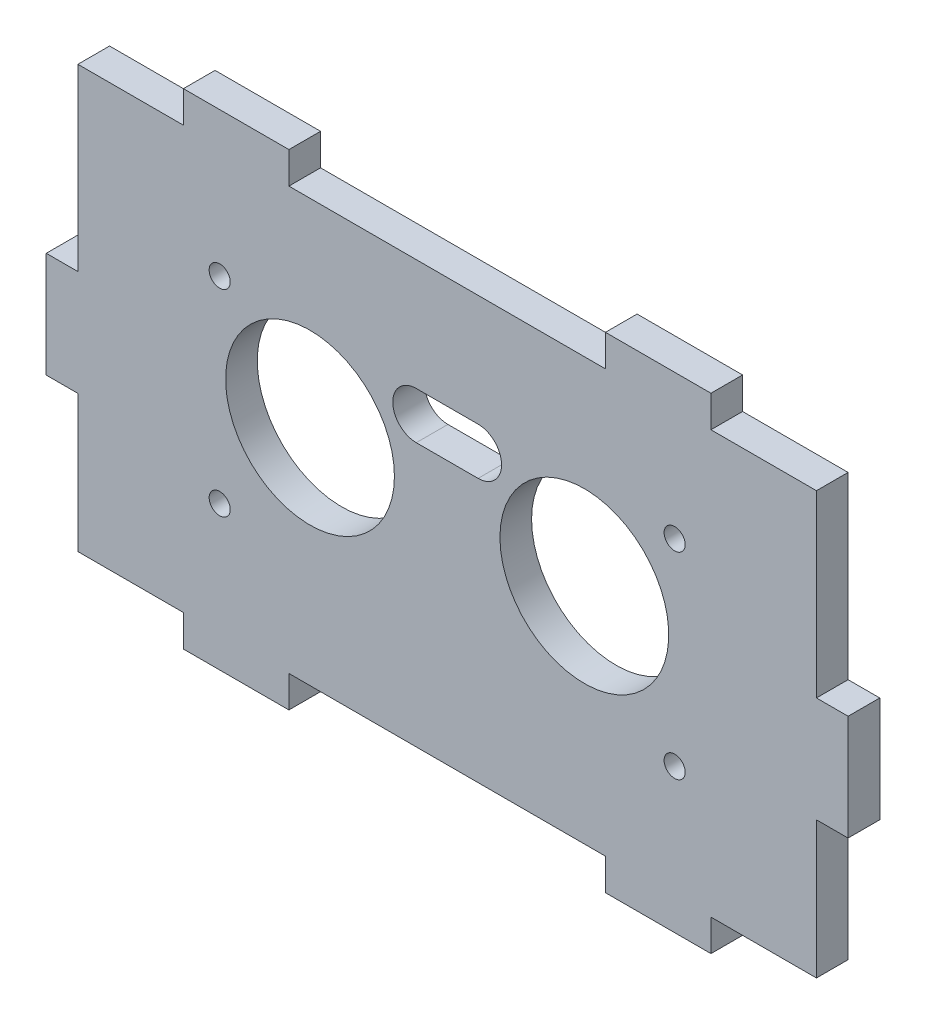
SolidWorks part; units mm, degrees
ref_plane "前视基准面" through (0, 0, 0) normal (0, 0, 1) x (1, 0, 0)
ref_plane "上视基准面" through (0, 0, 0) normal (0, 1, 0) x (1, 0, 0)
ref_plane "右视基准面" through (0, 0, 0) normal (1, 0, 0) x (0, 0, -1)
sketch "草图1" plane through (0, 0, 0) normal (0, 0, 1) x (1, 0, 0)
  line L0 (-35, -7.0139) -> (-35, -20)
  line L1 (-35, 20) -> (-25, 20)
  line L2 (-35, 20) -> (-35, 2.9861)
  line L3 (-35, -20) -> (-25, -20)
  line L4 (35, 20) -> (35, 2.9861)
  line L5 (-35, 20) -> (35, -20) construction
  line L6 (-35, -20) -> (35, 20) construction
  line L7 (-38, 2.9861) -> (-35, 2.9861)
  line L8 (-38, 2.9861) -> (-38, -7.0139)
  line L9 (-38, -7.0139) -> (-35, -7.0139)
  line L11 (-2.93, 7.2) -> (2.93, 7.2) construction
  line L12 (-2.93, 9.425) -> (2.93, 9.425)
  line L13 (0, 0) -> (0, 17.8715) construction
  line L14 (0, 0) -> (14.6737, 0) construction
  line L15 (38, -7.0139) -> (35, -7.0139)
  line L16 (38, 2.9861) -> (38, -7.0139)
  line L17 (38, 2.9861) -> (35, 2.9861)
  line L18 (35, -7.0139) -> (35, -20)
  line L19 (-15, -20) -> (15, -20)
  line L25 (-25, -20) -> (-25, -23)
  line L26 (-25, -23) -> (-15, -23)
  line L27 (-15, -20) -> (-15, -23)
  line L28 (25, -23) -> (15, -23)
  line L29 (15, -20) -> (15, -23)
  line L30 (25, -20) -> (25, -23)
  line L31 (25, 20) -> (25, 23)
  line L32 (25, 23) -> (15, 23)
  line L33 (15, 20) -> (15, 23)
  line L34 (-25, 20) -> (-25, 23)
  line L35 (-15, 20) -> (-15, 23)
  line L36 (-25, 23) -> (-15, 23)
  line L37 (-15, 20) -> (15, 20)
  line L38 (25, 20) -> (35, 20)
  line L39 (25, -20) -> (35, -20)
  line L40 (-2.93, 4.975) -> (2.93, 4.975)
  circle A0 centre (-13, 1.1716) radius 8
  circle A1 centre (13, 1.1716) radius 8
  arc A2 (-2.93, 9.425) -> (-2.93, 4.975) centre (-2.93, 7.2) ccw
  arc A3 (2.93, 4.975) -> (2.93, 9.425) centre (2.93, 7.2) ccw
  circle A5 centre (-21.56, 9.3416) radius 1
  circle A6 centre (-21.56, -9.3416) radius 1
  circle A7 centre (21.56, -9.3416) radius 1
  circle A8 centre (21.56, 9.3416) radius 1
  point P0 (0, 0)
  point P38 (0, 7.2)
  dimension "D6" = 16
  dimension "D1" = 40
  dimension "D2" = 70
  dimension "D3" = 10
  dimension "D4" = 3
  dimension "D5" = 10
  dimension "D7" = 13
  dimension "D8" = 5.86
  dimension "D9" = 4.45
  dimension "D10" = 7.2
  dimension "D11" = 8.17
  dimension "D12" = 21.56
extrude "凸台-拉伸1" add sketch "草图1" along normal blind 3
